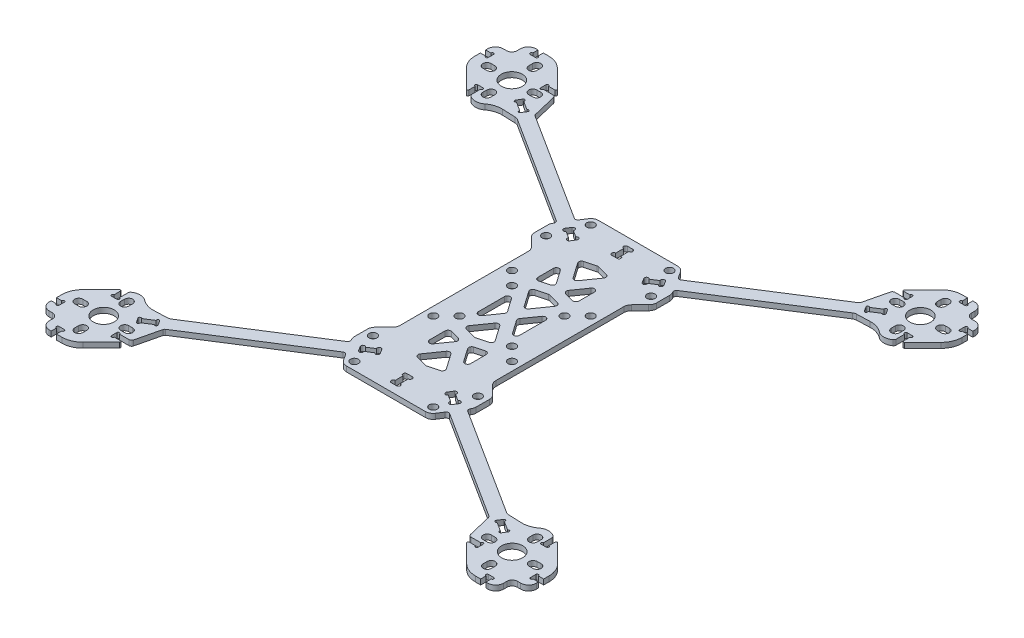
SolidWorks part; units mm, degrees
material "ABS"
ref_plane "Front Plane" through (0, 0, 0) normal (0, 0, 1) x (1, 0, 0)
ref_plane "Top Plane" through (0, 0, 0) normal (0, 1, 0) x (1, 0, 0)
ref_plane "Right Plane" through (0, 0, 0) normal (1, 0, 0) x (0, 0, -1)
sketch "Sketch11" plane through (0, 0, 0) normal (0, 1, 0) x (1, 0, 0)
  line L0 (0, 48.049) -> (0, 45.049)
  line L1 (0, 45.049) -> (1, 45.049)
  line L2 (1, 43.549) -> (1, 40.549)
  line L3 (0, 39.049) -> (1, 39.049)
  line L4 (0.9011, 5.5604) -> (4.9583, 11.3547)
  line L7 (18.23, 0) -> (18.23, 24.4052)
  line L8 (19.1087, 26.5265) -> (22.3513, 29.7692)
  line L9 (23.23, 31.8905) -> (23.23, 36.8905)
  line L11 (15.0325, 48.049) -> (0, 48.049)
  line L12 (13.9973, 38.2986) -> (16.5275, 39.9105)
  line L13 (17.7926, 40.7165) -> (18.8672, 39.0297)
  line L14 (17.6021, 38.2237) -> (15.0719, 36.6118)
  line L15 (12.7322, 37.4927) -> (13.8068, 35.8059)
  line L16 (-44.2539, 0) -> (44.2539, 0) construction
  line L17 (7.8346, 17.6869) -> (7.8346, 23.625)
  line L18 (4.3419, 13.0481) -> (0.2847, 14.1353)
  line L19 (2.3325, 0.6309) -> (5.8336, 5.6309)
  line L20 (7.8346, 5) -> (7.8346, 0)
  line L21 (2.1336, 0) -> (0, 0)
  line L22 (7.8346, 0) -> (18.23, 0)
  line L24 (0, 5.0913) -> (0, 0)
  line L25 (0, -44.7868) -> (0, 44.7868) construction
  line L26 (5.8336, 24.256) -> (2.3325, 19.256)
  line L27 (2.9489, 17.5625) -> (6.4499, 16.6244)
  line L28 (0.9011, 24.1854) -> (4.9614, 29.9842)
  line L29 (4.3451, 31.6776) -> (0.2847, 32.7656)
  line L30 (0, 32.8031) -> (0, 39.049)
  line L31 (0, 23.7163) -> (0, 14.1728)
  line L32 (69.8649, 82.8014) -> (69.8649, 80.8014)
  line L33 (68.8649, 82.8014) -> (66.4817, 82.8014)
  line L34 (68.8649, 80.8014) -> (65.1934, 80.8014)
  line L35 (64.2209, 80.0342) -> (62.0666, 71.034)
  line L38 (65.0651, 66.2851) -> (70.0381, 66.4711)
  line L39 (80.8649, 65.5802) -> (80.8649, 68.801)
  line L40 (80.8649, 69.801) -> (82.8649, 69.801)
  line L41 (82.8649, 68.801) -> (82.8649, 66.4178)
  line L42 (83.5477, 66.135) -> (90.5217, 73.109)
  line L43 (92.8649, 80.8014) -> (90.8649, 80.8014)
  line L44 (89.8649, 80.8014) -> (89.8649, 82.8014)
  line L45 (90.8649, 82.8014) -> (92.8649, 82.8014)
  line L46 (92.8649, 82.8014) -> (92.8649, 83.5514)
  line L47 (89.8649, 86.5514) -> (88.6149, 86.5514)
  line L48 (86.6149, 88.5514) -> (86.6149, 89.8014)
  line L49 (83.6149, 92.8014) -> (82.8649, 92.8014)
  line L50 (82.8649, 92.8014) -> (82.8649, 90.801)
  line L51 (80.8649, 90.801) -> (80.8649, 92.8014)
  line L52 (80.8649, 92.8014) -> (78.8297, 92.8014)
  line L53 (73.1729, 90.4583) -> (66.1989, 83.4842)
  line L55 (92.8649, 80.8014) -> (92.8649, 78.7659)
  line L56 (80.8649, 89.801) -> (82.8649, 89.801)
  line L57 (79.4149, 87.301) -> (79.4149, 85.801)
  line L58 (76.3149, 87.301) -> (76.3149, 85.801)
  line L59 (85.8649, 79.351) -> (87.3649, 79.351)
  line L60 (85.8649, 76.251) -> (87.3649, 76.251)
  line L61 (79.4149, 69.801) -> (79.4149, 68.301)
  line L62 (76.3149, 69.801) -> (76.3149, 68.301)
  line L63 (69.8649, 76.251) -> (68.3649, 76.251)
  line L64 (69.8649, 79.351) -> (68.3649, 79.351)
  line L68 (67.3228, 71.085) -> (77.8649, 77.801) construction
  line L69 (77.8649, 77.801) -> (85.8649, 77.801) construction
  line L70 (77.8649, 77.801) -> (77.8649, 85.801) construction
  line L71 (77.8649, 77.801) -> (69.8649, 77.801) construction
  line L72 (77.8649, 77.801) -> (77.8649, 69.801) construction
  line L73 (77.8649, 87.301) -> (77.8649, 85.801) construction
  line L74 (85.8649, 77.801) -> (87.3649, 77.801) construction
  line L75 (77.8649, 69.801) -> (77.8649, 68.301) construction
  line L76 (69.8649, 77.801) -> (68.3649, 77.801) construction
  line L77 (69.8649, 81.8014) -> (89.8649, 81.8014) construction
  line L78 (81.8649, 89.801) -> (81.8649, 69.801) construction
  line L79 (18.3299, 39.8731) -> (110.0192, 98.2856) construction
  line L80 (17.5626, 46.6609) -> (19.5168, 43.5934)
  line L81 (22.7602, 38.5024) -> (22.2033, 39.3765)
  line L82 (19.5168, 43.5934) -> (20.8601, 41.485) construction
  line L83 (20.8601, 41.485) -> (22.2033, 39.3765) construction
  line L84 (19.5168, 43.5934) -> (61.6314, 70.4234)
  line L85 (22.2033, 39.3765) -> (63.8433, 65.9041)
  line L86 (64.4659, 70.4506) -> (65.5405, 68.7638)
  line L87 (66.3839, 69.3011) -> (69.7574, 71.4503)
  line L88 (70.6008, 71.9876) -> (69.5262, 73.6744)
  line L89 (65.3093, 70.9879) -> (68.6828, 73.1371)
  arc A0 (1, 45.049) -> (1, 43.549) centre (1, 44.299) cw
  arc A1 (1, 39.049) -> (1, 40.549) centre (1, 39.799) ccw
  arc A2 (15.0325, 48.049) -> (17.5626, 46.6609) centre (15.0325, 45.049) cw
  arc A3 (22.7602, 38.5024) -> (23.23, 36.8905) centre (20.23, 36.8905) cw
  arc A4 (23.23, 31.8905) -> (22.3513, 29.7692) centre (20.23, 31.8905) cw
  arc A5 (19.1087, 26.5265) -> (18.23, 24.4052) centre (21.23, 24.4052) ccw
  arc A6 (17.7926, 40.7165) -> (16.5275, 39.9105) centre (17.16, 40.3135) ccw
  arc A7 (18.8672, 39.0297) -> (17.6021, 38.2237) centre (18.2346, 38.6267) cw
  arc A8 (13.8068, 35.8059) -> (15.0719, 36.6118) centre (14.4394, 36.2089) ccw
  arc A9 (12.7322, 37.4927) -> (13.9973, 38.2986) centre (13.3648, 37.8956) cw
  circle A10 centre (15.0325, 45.049) radius 1.5
  arc A13 (4.3419, 13.0481) -> (4.9583, 11.3547) centre (4.0572, 11.9856) cw
  arc A16 (0.9011, 5.5604) -> (0, 5.0913) centre (0, 6.1913) cw
  arc A17 (0.2847, 14.1353) -> (0, 14.1728) centre (0, 13.0728) ccw
  arc A18 (5.8336, 5.6309) -> (7.8346, 5) centre (6.7346, 5) cw
  arc A19 (2.3325, 0.6309) -> (2.1336, 0) centre (3.2336, 0) ccw
  arc A20 (7.8346, 23.625) -> (5.8336, 24.256) centre (6.7346, 23.625) ccw
  arc A21 (7.8346, 17.6869) -> (6.4499, 16.6244) centre (6.7346, 17.6869) cw
  arc A22 (2.3325, 19.256) -> (2.9489, 17.5625) centre (3.2336, 18.625) ccw
  arc A23 (4.3451, 31.6776) -> (4.9614, 29.9842) centre (4.0604, 30.6151) cw
  arc A24 (0.9011, 24.1854) -> (0, 23.7163) centre (0, 24.8163) cw
  arc A25 (0.2847, 32.7656) -> (0, 32.8031) centre (0, 31.7031) ccw
  circle A26 centre (10, 10) radius 1.5
  circle A27 centre (20, 33) radius 1.5
  arc A28 (66.1989, 83.4842) -> (66.4817, 82.8014) centre (66.4817, 83.2014) ccw
  arc A29 (69.8649, 82.8014) -> (68.8649, 82.8014) centre (69.3649, 82.8014) ccw
  arc A30 (69.8649, 80.8014) -> (68.8649, 80.8014) centre (69.3649, 80.8014) cw
  arc A31 (65.1934, 80.8014) -> (64.2209, 80.0342) centre (65.1934, 79.8014) ccw
  arc A36 (70.0381, 66.4711) -> (75.2028, 64.8268) centre (70.337, 58.4767) cw
  arc A37 (75.2028, 64.8268) -> (80.4572, 64.7744) centre (77.8649, 68.301) ccw
  arc A38 (80.8649, 65.5802) -> (80.4572, 64.7744) centre (79.8649, 65.5802) cw
  arc A39 (80.8649, 69.801) -> (80.8649, 68.801) centre (80.8649, 69.301) ccw
  arc A40 (82.8649, 69.801) -> (82.8649, 68.801) centre (82.8649, 69.301) cw
  arc A41 (82.8649, 66.4178) -> (83.5477, 66.135) centre (83.2649, 66.4178) ccw
  arc A42 (90.5217, 73.109) -> (92.8649, 78.7659) centre (84.8649, 78.7659) ccw
  arc A43 (89.8649, 86.5514) -> (92.8649, 83.5514) centre (89.8649, 83.5514) cw
  arc A44 (88.6149, 86.5514) -> (86.6149, 88.5514) centre (88.6149, 88.5514) cw
  arc A45 (86.6149, 89.8014) -> (83.6149, 92.8014) centre (83.6149, 89.8014) ccw
  arc A46 (78.8297, 92.8014) -> (73.1729, 90.4583) centre (78.8297, 84.8014) ccw
  arc A47 (76.3149, 87.301) -> (79.4149, 87.301) centre (77.8649, 87.301) cw
  arc A48 (76.3149, 85.801) -> (79.4149, 85.801) centre (77.8649, 85.801) ccw
  arc A49 (69.8649, 79.351) -> (69.8649, 76.251) centre (69.8649, 77.801) cw
  arc A50 (68.3649, 79.351) -> (68.3649, 76.251) centre (68.3649, 77.801) ccw
  arc A51 (82.8649, 89.801) -> (82.8649, 90.801) centre (82.8649, 90.301) ccw
  arc A52 (80.8649, 89.801) -> (80.8649, 90.801) centre (80.8649, 90.301) cw
  arc A53 (89.8649, 82.8014) -> (90.8649, 82.8014) centre (90.3649, 82.8014) cw
  arc A54 (89.8649, 80.8014) -> (90.8649, 80.8014) centre (90.3649, 80.8014) ccw
  arc A58 (75.4007, 74.6502) -> (73.9679, 76.8993) centre (77.8649, 77.801) ccw
  arc A60 (85.8649, 79.351) -> (85.8649, 76.251) centre (85.8649, 77.801) ccw
  arc A61 (87.3649, 79.351) -> (87.3649, 76.251) centre (87.3649, 77.801) cw
  arc A62 (79.4149, 69.801) -> (76.3149, 69.801) centre (77.8649, 69.801) ccw
  arc A63 (76.3149, 68.301) -> (79.4149, 68.301) centre (77.8649, 68.301) ccw
  arc A64 (73.9679, 76.8993) -> (75.4007, 74.6502) centre (77.8649, 77.801) ccw
  arc A65 (63.8433, 65.9041) -> (65.0651, 66.2851) centre (65.1565, 63.8429) cw
  arc A66 (61.6314, 70.4234) -> (62.0666, 71.034) centre (61.0941, 71.2668) ccw
  arc A67 (64.4659, 70.4506) -> (65.3093, 70.9879) centre (64.8876, 70.7193) cw
  arc A68 (69.5262, 73.6744) -> (68.6828, 73.1371) centre (69.1045, 73.4058) ccw
  arc A69 (70.6008, 71.9876) -> (69.7574, 71.4503) centre (70.1791, 71.719) cw
  arc A70 (65.5405, 68.7638) -> (66.3839, 69.3011) centre (65.9622, 69.0325) ccw
  circle A71 centre (15, 15) radius 1.5
  point P191 (79.8649, 81.8014)
  point P192 (81.8649, 79.801)
  point P193 (81.8649, 89.801)
  point P194 (89.8649, 81.8014)
  point P201 (65.0032, 69.6072)
  dimension "D2" = 3
  dimension "D3" = 3
  dimension "D4" = 3
  dimension "D5" = 3
  dimension "D11" = 3
  dimension "D19" = 0.75
  dimension "D20" = 0.75
  dimension "D21" = 5
  dimension "D22" = 1.1
  dimension "D23" = 1.1
  dimension "D26" = 5
  dimension "D28" = 1.1
  dimension "D9" = 1.1
  dimension "D25" = 1.1
  dimension "D32" = 1.1
  dimension "D33" = 1.1
  dimension "D34" = 1.1
  dimension "D35" = 1.1
  dimension "D36" = 1.1
  dimension "D37" = 1.1
  dimension "D39" = 3
  dimension "D43" = 3
  dimension "D49" = 1.55
  dimension "D50" = 0.5
  dimension "D52" = 4
  dimension "D61" = 0.4
  dimension "D62" = 1
  dimension "D63" = 4.3769
  dimension "D64" = 8
  dimension "D65" = 2.444
  dimension "D66" = 6
  dimension "D67" = 1
  dimension "D68" = 0.4
  dimension "D69" = 8
  dimension "D70" = 3
  dimension "D71" = 2
  dimension "D72" = 3
  dimension "D73" = 8
  dimension "D82" = 15
  dimension "D83" = 15
  dimension "D53" = 1
  dimension "D81" = 3
  dimension "D1" = 5
  dimension "D6" = 6
  dimension "D7" = 2
  dimension "D8" = 6
  dimension "D10" = 32.5
  dimension "D12" = 48.049
  dimension "D13" = 1
  dimension "D14" = 45
  dimension "D15" = 5
  dimension "D16" = 4.9954
  dimension "D17" = 9.4223
  dimension "D18" = 3
  dimension "D24" = 15
  dimension "D27" = 4
  dimension "D29" = 55
  dimension "D30" = 23.23
  dimension "D31" = 4
  dimension "D38" = 4
  dimension "D40" = 10
  dimension "D41" = 10
  dimension "D42" = 4
  dimension "D44" = 33
  dimension "D45" = 20
  dimension "D46" = 4.0004
  dimension "D47" = 8
  dimension "D48" = 1.5
  dimension "D51" = 2
  dimension "D54" = 3.6715
  dimension "D55" = 2
  dimension "D56" = 2
  dimension "D57" = 20
  dimension "D58" = 44.039
  dimension "D59" = 12.5
  dimension "D60" = 30.358
  dimension "D74" = 24.5353
  dimension "D75" = 0.75
  dimension "D76" = 2.0352
  dimension "D77" = 2.3832
  dimension "D78" = 3
  dimension "D79" = 2
  dimension "D80" = 55.34
  dimension "D84" = 0.75
  dimension "D85" = 1.25
  dimension "D86" = 3.2209
  dimension "D87" = 70.59
extrude "Boss-Extrude1" add sketch "Sketch11" along normal blind 2
mirror "Mirror10" about plane through (0, 0, 0) normal (1, 0, 0) of "Boss-Extrude1"
mirror "Mirror11" about plane through (0, 0, 0) normal (0, 0, 1) of "Mirror10", "Boss-Extrude1"
fillet "Fillet1" radius 1 8 edges at (22.2033, 1, 39.3765) (19.5168, 1, 43.5934) (-19.5168, 1, 43.5934) (-22.2033, 1, 39.3765) (-22.2033, 1, -39.3765) (-19.5168, 1, -43.5934) (19.5168, 1, -43.5934) (22.2033, 1, -39.3765)
